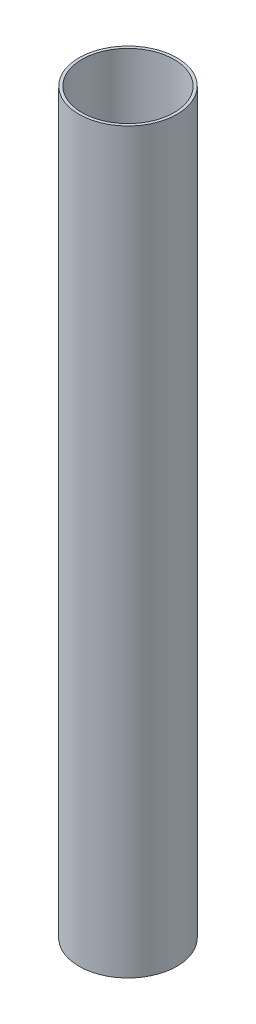
SolidWorks part; units mm, degrees
ref_plane "Front Plane" through (0, 0, 0) normal (0, 0, 1) x (1, 0, 0)
ref_plane "Top Plane" through (0, 0, 0) normal (0, 1, 0) x (1, 0, 0)
ref_plane "Right Plane" through (0, 0, 0) normal (1, 0, 0) x (0, 0, -1)
sketch "Sketch1" plane through (0, 0, 0) normal (0, 1, 0) x (1, 0, 0)
  circle A0 centre (0, 0) radius 53.975
  circle A1 centre (0, 0) radius 50.8
  dimension "D1" = 107.95
  dimension "D2" = 101.6
extrude "Boss-Extrude1" add sketch "Sketch1" along normal mid plane 812.8
equation "\"airframeInnerDiameter\"= 6in"
equation "\"outerDiameter\"= 6.112in"
equation "\"airframeBulkheadThickness\"= 0.125in"
equation "\"payloadAirframeLength\"= 10in"
equation "\"payloadInnerDiameter\"= 6in - 0.056in"
equation "\"payloadOuterDiameter\"= \"airframeInnerDiameter\""
equation "\"payloadLength\"= 11in"
equation "\"payloadBand\"= 2in"
equation "\"payloadOffsetFromAft\"= 6in"
equation "\"upperAirframeLength\"= 25in"
equation "\"recoveryBayInnerDiameter\"= 5.888in"
equation "\"recoveryLength\"= 8in"
equation "\"recoveryBand\"= 2in"
equation "\"recoveryCouplerOuter\"=\"airframeInnerDiameter\""
equation "\"recoveryOffsetFromAft\"= 3in"
equation "\"midAirframeLength\"= 20in"
equation "\"atsLength\"= 11in"
equation "\"atsInner\"= 5.888in"
equation "\"atsBand\"= 2in"
equation "\"atsCouplerOuter\"=\"airframeInnerDiameter\""
equation "\"atsOffsetFromAft\"= 3in"
equation "\"lowerAirframeLength\"= 40in"
equation "\"motorTubeOuterDiameter\"= 4.25in"
equation "\"motorTubeInnerDiameter\"= 4in"
equation "\"motorTubeLength\"= 32in"
equation "\"centeringRingOuterDiameter\"= \"airframeInnerDiameter\""
equation "\"centeringRingInnerDiameter\"= \"motorTubeOuterDiameter\""
equation "\"centeringRingThickness\"= 0.375in"
equation "\"topCenteringRingOffsetFromAft\"= 16.7in"
equation "\"bottomCenteringRingOffsetFromAft\"= 0.3in"
equation "\"finSlotLength\"= 8in"
equation "\"finSlotOffsetFromAft\"= 3in"
equation "\"finSlotWidth\"= 0.187in"
equation "\"D1@Sketch1\"=\"motorTubeOuterDiameter\""
equation "\"D2@Sketch1\"=\"motorTubeInnerDiameter\""
equation "\"D1@Boss-Extrude1\"=\"motorTubeLength\""
